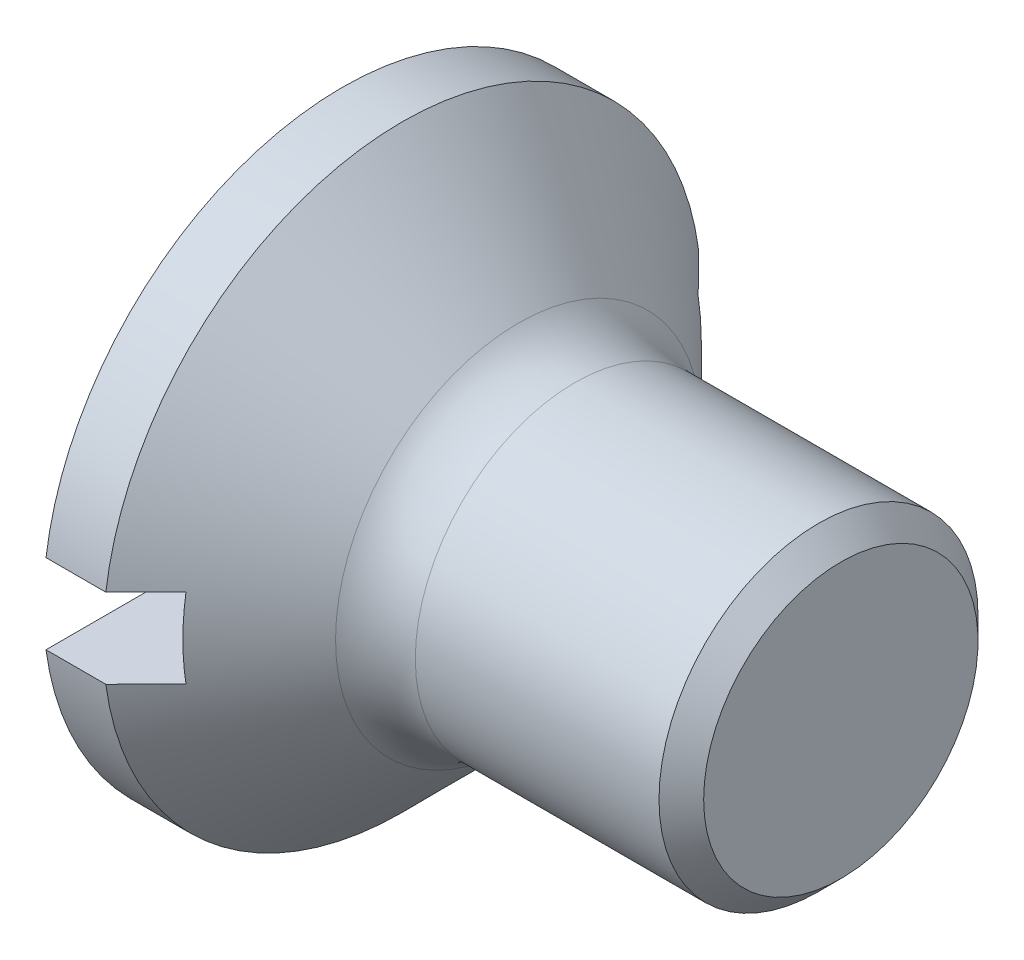
SolidWorks part; units mm, degrees
ref_plane "Přední rovina" through (0, 0, 0) normal (0, 0, 1) x (1, 0, 0)
ref_plane "Vrchní rovina" through (0, 0, 0) normal (0, 1, 0) x (1, 0, 0)
ref_plane "Pravá rovina" through (0, 0, 0) normal (1, 0, 0) x (0, 0, -1)
sketch "Skica1" plane through (0, 0, 0) normal (0, 0, 1) x (1, 0, 0)
  line L0 (0, 0) -> (0, 1.5)
  line L1 (0, 1.5) -> (0.3, 1.5)
  line L2 (0.3, 1.5) -> (1, 0.8)
  line L3 (1, 0.8) -> (2.5, 0.8)
  line L4 (2.5, 0.8) -> (2.5, 0)
  line L5 (2.5, 0) -> (0, 0)
  line L6 (0, 0) -> (-18.1984, 0) construction
  dimension "M" = 1.6
  dimension "l" = 2.5
  dimension "k" = 1
  dimension "D4" = 45
  dimension "D" = 3
revolve "Otočit kolem osy1" add sketch "Skica1" angle 360 about L6
cosmetic thread "Kosmetický závit1" parameters "D1"=1.33, "D2"=1.36
fillet "Zaoblit1" radius 0.4 1 edges at (1, 0, -0.8)
chamfer "Zkosit1" distance 0.112 angle 45 1 edges at (2.5, 0, -0.8)
sketch "Skica2" plane through (0, 0, 0) normal (-1, 0, 0) x (0, 0, 1)
  line L0 (0, 0) -> (1.5, 0) construction
  line L1 (-1.5, 0.2) -> (1.5, 0.2)
  line L2 (-1.5, 0.2) -> (-1.5, -0.2)
  line L3 (-1.5, -0.2) -> (1.5, -0.2)
  line L4 (1.5, 0.2) -> (1.5, -0.2)
  circle A0 centre (0, 0) radius 1.5 construction
  dimension "n" = 0.4
extrude "Odebrat vysunutím1" cut sketch "Skica2" against normal blind 0.5
equation "\"D1@Zkosit1\" = 0.07*\"M@Skica1\""
equation "\"D2@Kosmetický závit1\" = \"M@Skica1\" * 0.85"
